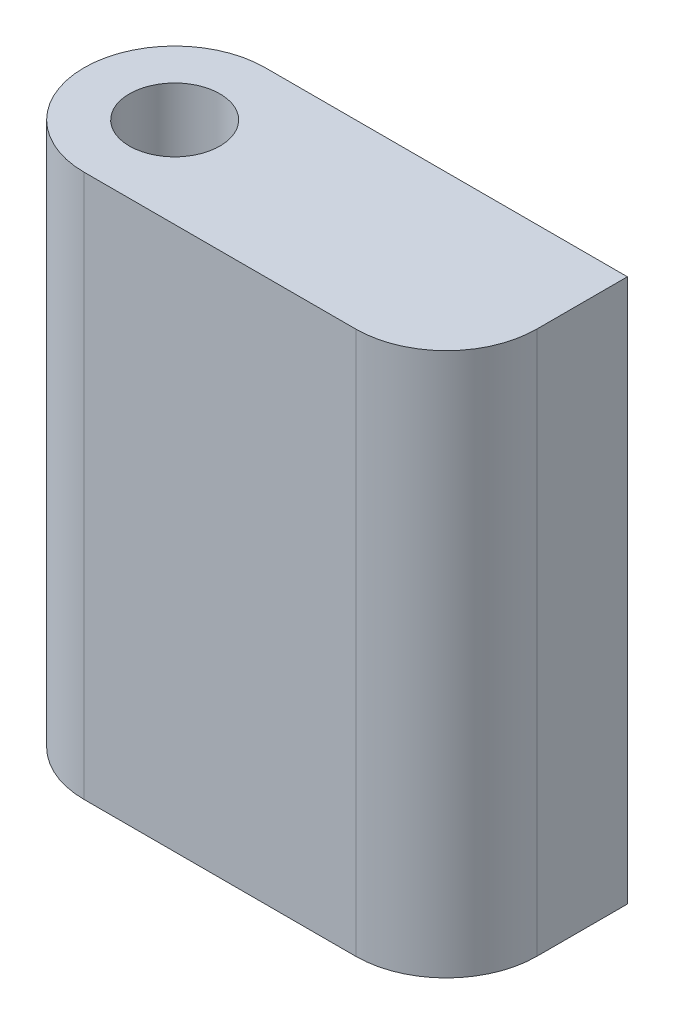
SolidWorks part; units mm, degrees
ref_plane "Front Plane" through (0, 0, 0) normal (0, 0, 1) x (1, 0, 0)
ref_plane "Top Plane" through (0, 0, 0) normal (0, 1, 0) x (1, 0, 0)
ref_plane "Right Plane" through (0, 0, 0) normal (1, 0, 0) x (0, 0, -1)
sketch "Sketch1" plane through (0, 0, 0) normal (0, 1, 0) x (1, 0, 0)
  line L0 (0, 5) -> (20, 5)
  line L1 (20, -5) -> (0, -5)
  line L2 (20, 5) -> (20, -5)
  circle A0 centre (0, 0) radius 2.5
  arc A1 (0, 5) -> (0, -5) centre (0, 0) ccw
  dimension "D1" = 5
  dimension "D2" = 10
  dimension "D3" = 20
extrude "Boss-Extrude1" add sketch "Sketch1" along normal blind 30
fillet "Fillet1" radius 5 1 edges at (20, 15, 5)
